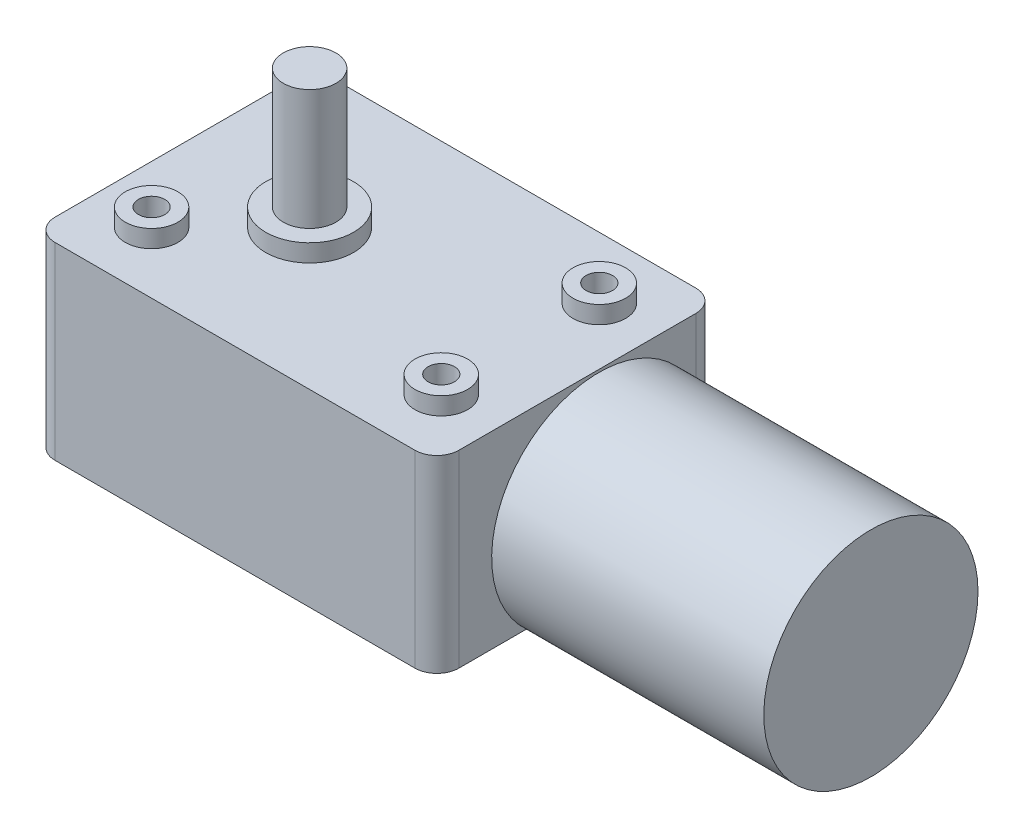
SolidWorks part; units mm, degrees
ref_plane "Front Plane" through (0, 0, 0) normal (0, 0, 1) x (1, 0, 0)
ref_plane "Top Plane" through (0, 0, 0) normal (0, 1, 0) x (1, 0, 0)
ref_plane "Right Plane" through (0, 0, 0) normal (1, 0, 0) x (0, 0, -1)
sketch "Sketch1" plane through (0, 0, 0) normal (0, 1, 0) x (1, 0, 0)
  line L1 (-20.5, -16) -> (20.5, -16)
  line L2 (-23, -13.5) -> (-23, 13.5)
  line L3 (-20.5, 16) -> (20.5, 16)
  line L4 (23, -13.5) -> (23, 13.5)
  line L5 (-23, -16) -> (23, 16) construction
  line L6 (-23, 16) -> (23, -16) construction
  arc A0 (-23, -13.5) -> (-20.5, -16) centre (-20.5, -13.5) ccw
  arc A1 (20.5, -16) -> (23, -13.5) centre (20.5, -13.5) ccw
  arc A2 (23, 13.5) -> (20.5, 16) centre (20.5, 13.5) ccw
  arc A3 (-23, 13.5) -> (-20.5, 16) centre (-20.5, 13.5) cw
  point P0 (0, 0)
  dimension "D3" = 2.5
  dimension "D1" = 46
  dimension "D2" = 32
extrude "Boss-Extrude1" add sketch "Sketch1" along normal mid plane 21.5
sketch "Sketch2" plane through (0, 10.75, 0) normal (0, 1, 0) x (1, 0, 0)
  line L0 (-1000, 0) -> (49000, 0) construction
  line L1 (-1000.4558, 9) -> (48999.5442, 9) construction
  line L2 (-1000.9116, -9) -> (48999.0884, -9) construction
  line L3 (-16.5, -994.0746) -> (-16.5, 49005.9254) construction
  line L4 (16.5, -995.2141) -> (16.5, 49004.7859) construction
  line L5 (-23, 13.5) -> (-23, -13.5) construction
  circle A0 centre (-16.5, 9) radius 3
  circle A1 centre (-16.5, -9) radius 3
  circle A2 centre (16.5, -9) radius 3
  circle A3 centre (16.5, 9) radius 3
  circle A4 centre (-7.5, 0) radius 5
  dimension "D5" = 6
  dimension "D6" = 6
  dimension "D7" = 6
  dimension "D8" = 6
  dimension "D9" = 10
  dimension "D1" = 9
  dimension "D2" = 9
  dimension "D3" = 6.5
  dimension "D4" = 33
  dimension "D10" = 15.5
extrude "Boss-Extrude2" add sketch "Sketch2" along normal blind 2
sketch "Sketch3" plane through (0, 12.75, 0) normal (0, 1, 0) x (1, 0, 0)
  circle A0 centre (-16.5, 9) radius 1.5
  circle A1 centre (16.5, 9) radius 1.5
  circle A2 centre (16.5, -9) radius 1.5
  circle A3 centre (-16.5, -9) radius 1.5
  dimension "D1" = 3
  dimension "D2" = 3
  dimension "D3" = 3
  dimension "D4" = 3
extrude "Cut-Extrude1" cut sketch "Sketch3" against normal blind 6
sketch "Sketch4" plane through (0, 12.75, 0) normal (0, 1, 0) x (1, 0, 0)
  circle A0 centre (-7.5, 0) radius 3
  dimension "D1" = 6
extrude "Boss-Extrude3" add sketch "Sketch4" along normal blind 13.7
sketch "Sketch5" plane through (23, 0, 0) normal (1, 0, 0) x (0, 0, -1)
  line L0 (-13.5, 10.75) -> (13.5, 10.75) construction
  circle A0 centre (2.4367, -1.75) radius 12.2
  dimension "D2" = 24.4
  dimension "D1" = 3
  dimension "D3" = 12.5
extrude "Boss-Extrude4" add sketch "Sketch5" along normal blind 31
